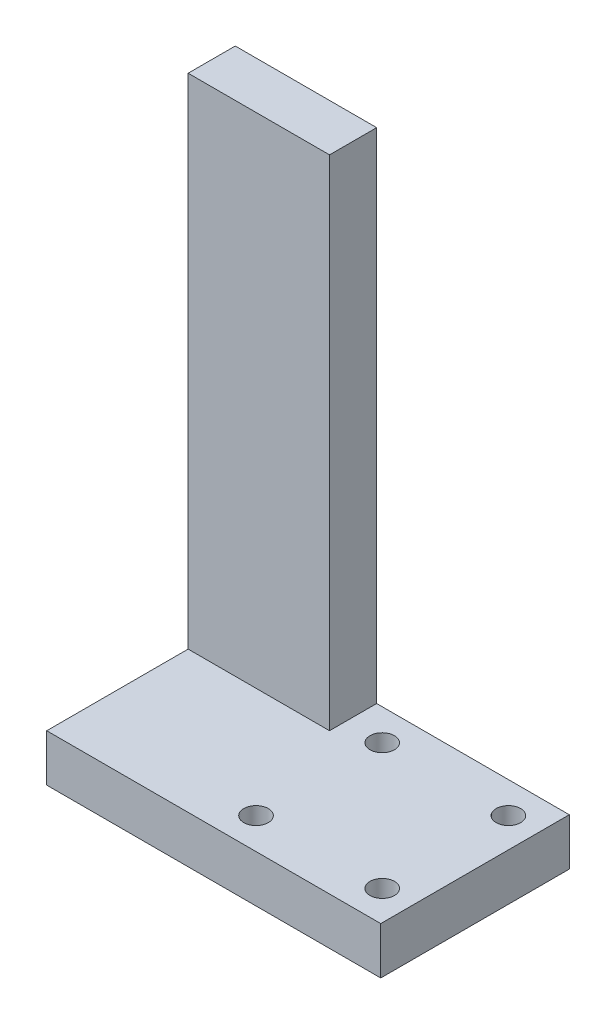
SolidWorks part; units mm, degrees
material "6061-O (SS)"
ref_plane "Alzado" through (0, 0, 0) normal (0, 0, 1) x (1, 0, 0)
ref_plane "Planta" through (0, 0, 0) normal (0, 1, 0) x (1, 0, 0)
ref_plane "Vista lateral" through (0, 0, 0) normal (1, 0, 0) x (0, 0, -1)
sketch "Croquis1" plane through (0, 0, 0) normal (0, 1, 0) x (1, 0, 0)
  line L1 (45, 25.4) -> (-45, 25.4)
  line L2 (45, 25.4) -> (45, -25.4)
  line L3 (45, -25.4) -> (-45, -25.4)
  line L4 (-45, 25.4) -> (-45, -25.4)
  line L5 (45, 25.4) -> (-45, -25.4) construction
  line L6 (45, -25.4) -> (-45, 25.4) construction
  point P0 (0, 0)
  dimension "D1" = 50.8
  dimension "D2" = 90
extrude "Saliente-Extruir1" add sketch "Croquis1" along normal mid plane 12.7
hole_wizard "Taladro de margen para M61" positions "Croquis2" profile "Croquis3" hole size "M6" standard "Ansi Metric" end condition through all
sketch "Croquis2" plane through (0, -6.35, 0) normal (0, -1, 0) x (-1, 0, 0)
  point P0 (-36.5837, -75.7254)
  point P2 (-37, -17)
  point P5 (-37, 17)
  point P8 (-3, -17)
  point P11 (-3, 17)
sketch "Croquis3" plane through (36.5837, -6.35, 75.7254) normal (1, 0, 0) x (0, 0, -1)
  line L0 (0, 0) -> (0, 12.7)
  line L1 (0, 12.7) -> (3.3, 12.7)
  line L2 (3.3, 12.7) -> (3.3, 0)
  line L5 (3.3, 0) -> (0, 0)
  line L11 (0, -6.35) -> (0, 107.95) construction
  dimension "Diámetro de taladro hasta el siguiente" = 6.6
  dimension "Profundidad de taladro hasta el siguiente" = 12.7
sketch "Croquis4" plane through (0, 6.35, 0) normal (0, 1, 0) x (1, 0, 0)
  line L0 (45, 25.4) -> (-45, 25.4) construction
  line L1 (-6.9, 25.4) -> (-45, 25.4)
  line L2 (-6.9, 25.4) -> (-6.9, 12.7)
  line L3 (-6.9, 12.7) -> (-45, 12.7)
  line L4 (-45, 25.4) -> (-45, 12.7)
  dimension "D1" = 12.7
  dimension "D2" = 38.1
extrude "Saliente-Extruir2" add sketch "Croquis4" along normal blind 134.38
